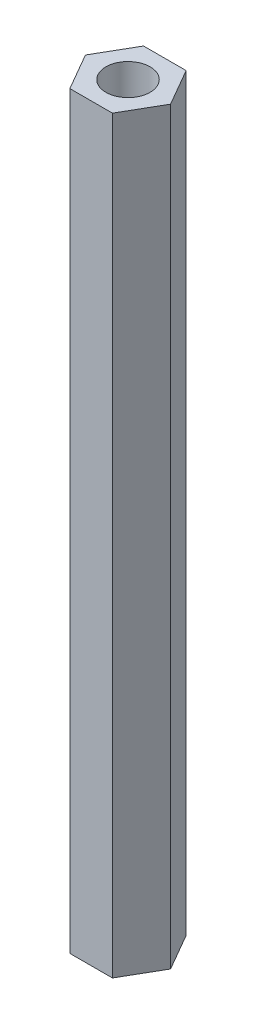
SolidWorks part; units mm, degrees
ref_plane "Front Plane" through (0, 0, 0) normal (0, 0, 1) x (1, 0, 0)
ref_plane "Top Plane" through (0, 0, 0) normal (0, 1, 0) x (1, 0, 0)
ref_plane "Right Plane" through (0, 0, 0) normal (1, 0, 0) x (0, 0, -1)
sketch "Sketch1" plane through (0, 0, 0) normal (0, 1, 0) x (1, 0, 0)
  line L1 (2.8868, 0) -> (1.4434, 2.5)
  line L2 (1.4434, 2.5) -> (-1.4434, 2.5)
  line L3 (-1.4434, 2.5) -> (-2.8868, 0)
  line L4 (-2.8868, 0) -> (-1.4434, -2.5)
  line L5 (-1.4434, -2.5) -> (1.4434, -2.5)
  line L6 (1.4434, -2.5) -> (2.8868, 0)
  circle A0 centre (0, 0) radius 2.5 construction
  dimension "D1" = 5
extrude "Boss-Extrude1" add sketch "Sketch1" along normal blind 50.8
sketch "Sketch2" plane through (0, 50.8, 0) normal (0, 1, 0) x (1, 0, 0)
  circle A0 centre (0, 0) radius 1.5
  dimension "D1" = 3
extrude "Cut-Extrude1" cut sketch "Sketch2" against normal through all
